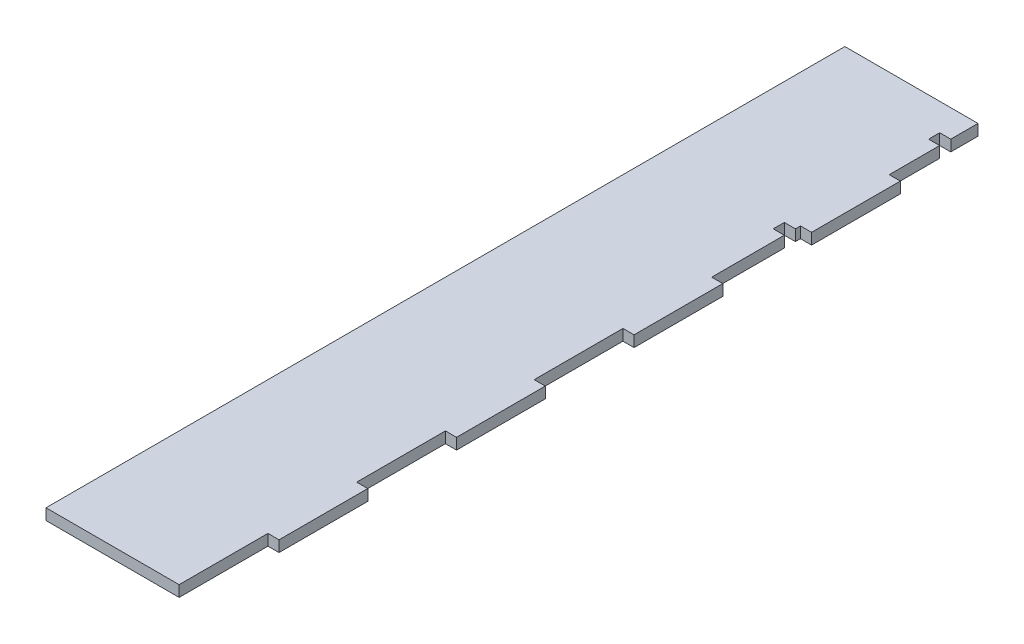
SolidWorks part; units mm, degrees
ref_plane "Front Plane" through (0, 0, 0) normal (0, 0, 1) x (1, 0, 0)
ref_plane "Top Plane" through (0, 0, 0) normal (0, 1, 0) x (1, 0, 0)
ref_plane "Right Plane" through (0, 0, 0) normal (1, 0, 0) x (0, 0, -1)
sketch "Sketch1" plane through (0, 0, 0) normal (0, 0, 1) x (1, 0, 0)
  line L1 (-38.1, -38.1) -> (38.1, -38.1) construction
  line L2 (-38.1, -38.1) -> (-38.1, 38.1) construction
  line L3 (-38.1, 38.1) -> (38.1, 38.1) construction
  line L4 (38.1, -38.1) -> (38.1, 38.1) construction
  line L5 (-38.1, -38.1) -> (38.1, 38.1) construction
  line L6 (-38.1, 38.1) -> (38.1, -38.1) construction
  line L7 (-38.1, -38.1) -> (38.1, -38.1)
  line L8 (-38.1, -38.1) -> (-38.1, -44.45)
  line L9 (-38.1, -44.45) -> (38.1, -44.45)
  line L10 (38.1, -38.1) -> (38.1, -44.45)
  point P0 (0, 0)
  dimension "D1" = 76.2
  dimension "D2" = 6.35
extrude "Boss-Extrude1" add sketch "Sketch1" along normal blind 457.2
sketch "Sketch2" plane through (38.1, 0, 0) normal (1, 0, 0) x (0, 0, -1)
  line L0 (-457.2, -44.45) -> (0, -44.45) construction
  line L1 (-406.4, -44.45) -> (-355.6, -44.45)
  line L2 (-406.4, -44.45) -> (-406.4, -38.1)
  line L3 (-406.4, -38.1) -> (-355.6, -38.1)
  line L4 (-355.6, -44.45) -> (-355.6, -38.1)
  line L5 (-406.4, -44.45) -> (-406.4, -38.1) construction
  line L6 (-355.6, -38.1) -> (-355.6, -44.45) construction
  line L7 (-457.2, -38.1) -> (0, -38.1) construction
  line L8 (-304.8, -44.45) -> (-304.8, -38.1) construction
  line L9 (-304.8, -44.45) -> (-254, -44.45)
  line L10 (-304.8, -44.45) -> (-304.8, -38.1)
  line L11 (-304.8, -38.1) -> (-254, -38.1)
  line L12 (-254, -44.45) -> (-254, -38.1)
  line L13 (-203.2, -44.45) -> (-152.4, -44.45)
  line L14 (-203.2, -44.45) -> (-203.2, -38.1)
  line L15 (-203.2, -38.1) -> (-152.4, -38.1)
  line L16 (-152.4, -44.45) -> (-152.4, -38.1)
  line L17 (-101.6, -44.45) -> (-50.8, -44.45)
  line L18 (-101.6, -44.45) -> (-101.6, -38.1)
  line L19 (-101.6, -38.1) -> (-50.8, -38.1)
  line L20 (-50.8, -44.45) -> (-50.8, -38.1)
  line L21 (-254, -38.1) -> (-254, -44.45) construction
  line L22 (-203.2, -44.45) -> (-203.2, -38.1) construction
  line L23 (-152.4, -38.1) -> (-152.4, -44.45) construction
  line L24 (-101.6, -44.45) -> (-101.6, -38.1) construction
  line L25 (-50.8, -38.1) -> (-50.8, -44.45) construction
extrude "Boss-Extrude2" add sketch "Sketch2" along normal up to surface (6.35 mm away)
sketch "Sketch3" plane through (0, -38.1, 0) normal (0, 1, 0) x (1, 0, 0)
  line L0 (38.1, -152.4) -> (38.1, -101.6) construction
  line L1 (31.75, -104.4875) -> (38.1, -104.4875)
  line L2 (31.75, -104.4875) -> (31.75, -110.8375)
  line L3 (31.75, -110.8375) -> (38.1, -110.8375)
  line L4 (38.1, -104.4875) -> (38.1, -110.8375)
extrude "Cut-Extrude1" cut sketch "Sketch3" against normal blind 6.35
sketch "Sketch4" plane through (0, -38.1, 0) normal (0, 1, 0) x (1, 0, 0)
  line L0 (38.1, -50.8) -> (38.1, 0) construction
  line L1 (31.75, -21.9375) -> (38.1, -21.9375)
  line L2 (31.75, -21.9375) -> (31.75, -15.5875)
  line L3 (31.75, -15.5875) -> (38.1, -15.5875)
  line L4 (38.1, -21.9375) -> (38.1, -15.5875)
extrude "Cut-Extrude2" cut sketch "Sketch4" against normal through all
